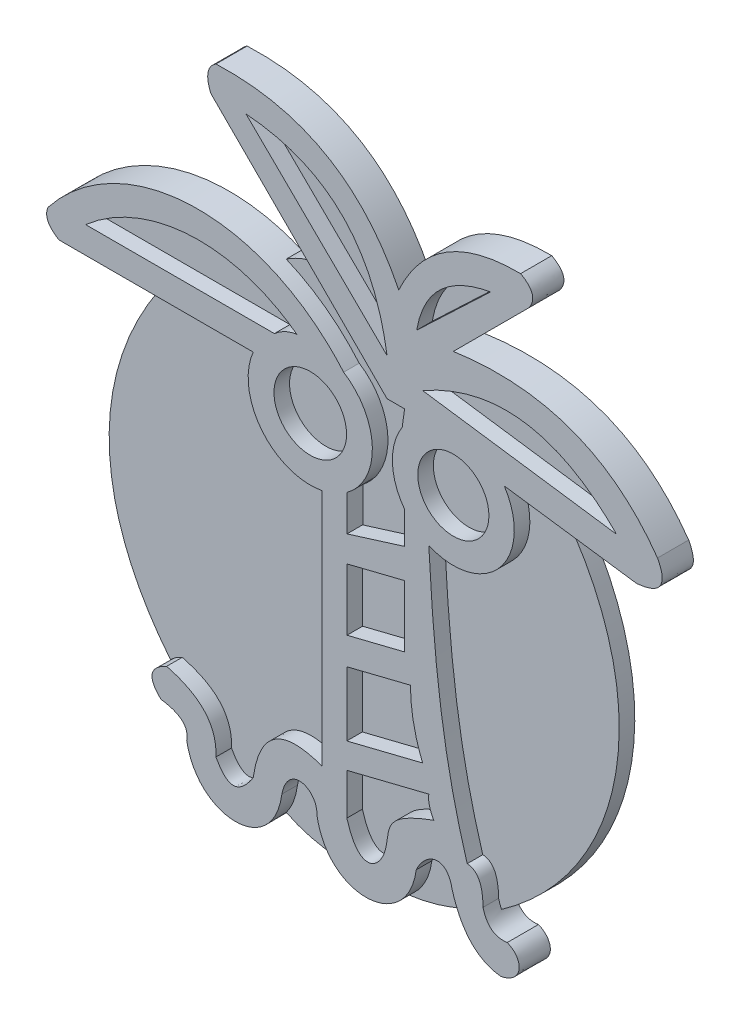
SolidWorks part; units mm, degrees
ref_plane "Plano frontal" through (0, 0, 0) normal (0, 0, 1) x (1, 0, 0)
ref_plane "Plano superior" through (0, 0, 0) normal (0, 1, 0) x (1, 0, 0)
ref_plane "Plano direito" through (0, 0, 0) normal (1, 0, 0) x (0, 0, -1)
sketch "Esboço1" plane through (0, 0, 0) normal (0, 0, 1) x (1, 0, 0)
  line L0 (-60.8884, 28.3736) -> (-123.2049, 28.3736)
  line L1 (-114.6677, 36.9122) -> (-54.103, 36.9122)
  line L2 (-38.7824, 0.9277) -> (-38.7824, -75.6639)
  line L3 (-30.8012, 4.4193) -> (-30.8012, -7.0977)
  line L4 (-30.8012, -7.0977) -> (-12.3205, -1.3392)
  line L5 (-12.3205, -1.3392) -> (-12.3205, 8.9725)
  line L6 (-30.8012, -15.4417) -> (-12.3205, -10.8474)
  line L7 (-12.3205, -10.8474) -> (-12.3205, -30.6673)
  line L8 (-12.3205, -30.6673) -> (-30.8012, -35.2616)
  line L9 (-30.8012, -35.2616) -> (-30.8012, -15.4417)
  line L10 (-30.8149, -44.0341) -> (-10.4456, -38.9702)
  line L11 (-6.5434, -58.6334) -> (-30.8763, -64.6826)
  line L12 (-30.8763, -64.6826) -> (-30.8149, -44.0341)
  line L13 (-30.8481, -72.8265) -> (-4.5532, -66.2896)
  line L14 (-30.8481, -72.8265) -> (-30.8481, -86.1095)
  line L15 (19.6685, 31.4554) -> (62.1381, 25.5784)
  line L16 (3.3205, 60.665) -> (27.6404, 84.9849)
  line L17 (-74.4586, 93.402) -> (-17.9451, 36.8885)
  line L18 (-17.9451, 36.8885) -> (-12.3205, 36.8885)
  line L19 (-12.3205, 36.8885) -> (-13.0844, 31.3682)
  line L20 (-63.2095, 93.402) -> (-17.9451, 48.8802)
  line L21 (-6.5434, 44.8627) -> (55.71, 36.024)
  line L22 (-8.4456, 60.665) -> (15.2667, 83.1633)
  arc A0 (-60.8884, 28.3736) -> (-38.7824, 0.9277) centre (-42.586, 20.4895) ccw
  circle A1 centre (-106.0634, -77.5387) radius 4.9451
  arc A3 (-4.5532, 2.8123) -> (19.6685, 31.4554) centre (3.3205, 20.7169) ccw
  arc A4 (-13.0844, 31.3682) -> (-12.3205, 8.9725) centre (3.3205, 20.7169) ccw
  circle A5 centre (-42.586, 20.4895) radius 11.6455
  circle A6 centre (3.3205, 20.7169) radius 11.4162
  arc A7 (-30.8012, 4.4193) -> (-31.8683, 37.2902) centre (-42.586, 20.4895) ccw
  spline S0 degree 3 poles (-126.6868, 35.7562) (-102.8055, 65.8868) (-57.2496, 68.1638) (-30.8012, 36.024) knots 0 0 0 0 1 1 1 1
  spline S1 degree 2 poles (-123.2049, 28.3736) (-128.5563, 31.5723) (-126.6868, 35.7562) knots 0 0 0 1 1 1
  spline S2 degree 3 poles (-114.6677, 36.9122) (-95.4732, 53.7124) (-67.6287, 55.71) (-46.8714, 40.3094) knots 0 0 0 0 1 1 1 1
  spline S3 degree 2 poles (-54.103, 36.9122) (-50.7611, 39.8144) (-46.8714, 40.3094) knots 0 0 0 1 1 1
  spline S4 degree 2 poles (-10.4456, -38.9702) (-10.4151, -49.1245) (-6.5434, -58.6334) knots 0 0 0 1 1 1
  spline S5 degree 2 poles (-4.5532, -66.2896) (-4.9343, -69.3953) (-2.9462, -72.7552) knots 0 0 0 1 1 1
  spline S6 degree 3 poles (-30.8481, -86.1095) (-27.1078, -99.4978) (-18.8735, -94.8712) (-17.4742, -81.1051) (-15.668, -77.3953) (-2.9462, -72.7552) knots 0 0 0 0 0.568309 0.668309 1 1 1 1
  spline S7 degree 3 poles (-4.5532, 2.8123) (-2.8793, -27.9871) (-0.2678, -53.0855) (7.7673, -79.468) knots 0 0 0 0 1 1 1 1
  spline S8 degree 2 poles (7.7673, -79.468) (12.7783, -79.7342) (12.8562, -89.0557) knots 0 0 0 1 1 1
  spline S9 degree 2 poles (12.8562, -89.0557) (14.5282, -95.7441) (20.6234, -94.9481) knots 0 0 0 1 1 1
  spline S10 degree 3 poles (20.6234, -94.9481) (26.2001, -97.1788) (25.846, -104.0546) (18.4807, -105.3938) knots 0 0 0 0 1 1 1 1
  spline S11 degree 2 poles (18.4807, -105.3938) (7.2976, -104.1184) (2.9462, -89.0557) knots 0 0 0 1 1 1
  spline S12 degree 3 poles (2.9462, -89.0557) (1.2727, -80.3537) (-5.6695, -82.8514) (-8.5708, -89.3236) knots 0 0 0 0 1 1 1 1
  spline S13 degree 3 poles (-8.5708, -89.3236) (-11.2487, -109.408) (-36.7608, -110.8833) (-40.4434, -90.1271) knots 0 0 0 0 1 1 1 1
  spline S14 degree 3 poles (-40.4434, -90.1271) (-40.1086, -83.0964) (-49.6838, -79.4808) (-51.6925, -89.8592) knots 0 0 0 0 1 1 1 1
  spline S15 degree 3 poles (-51.6925, -89.8592) (-54.3704, -110.2785) (-78.8779, -109.5451) (-82.2259, -90.1271) knots 0 0 0 0 1 1 1 1
  spline S16 degree 2 poles (-82.2259, -90.1271) (-81.1547, -84.2346) (-90.5288, -82.8955) knots 0 0 0 1 1 1
  spline S17 degree 2 poles (-90.5288, -82.8955) (-97.023, -76.7076) (-88.654, -72.8265) knots 0 0 0 1 1 1
  spline S18 degree 2 poles (-88.654, -72.8265) (-72.2554, -77.0412) (-72.8516, -90.1271) knots 0 0 0 1 1 1
  spline S19 degree 3 poles (-72.8516, -90.1271) (-69.5068, -96.3708) (-65.7853, -97.5389) (-60.8884, -89.8592) knots 0 0 0 0 1 1 1 1
  spline S20 degree 2 poles (-60.8884, -89.8592) (-57.9268, -68.6355) (-38.7824, -75.6639) knots 0 0 0 1 1 1
  spline S21 degree 2 poles (62.1381, 25.5784) (73.854, 26.6535) (68.834, 36.024) knots 0 0 0 1 1 1
  spline S22 degree 2 poles (68.834, 36.024) (47.0455, 67.0261) (3.3205, 60.665) knots 0 0 0 1 1 1
  spline S23 degree 2 poles (27.6404, 84.9849) (30.9295, 89.7285) (24.9088, 93.0733) knots 0 0 0 1 1 1
  spline S24 degree 2 poles (24.9088, 93.0733) (-2.8772, 93.408) (-14.1953, 68.968) knots 0 0 0 1 1 1
  spline S25 degree 2 poles (-14.1953, 68.968) (-31.6027, 104.1174) (-72.8516, 102.4476) knots 0 0 0 1 1 1
  spline S26 degree 2 poles (-72.8516, 102.4476) (-77.1364, 99.6857) (-74.4586, 93.402) knots 0 0 0 1 1 1
  spline S27 degree 2 poles (-63.2095, 93.402) (-24.306, 90.3936) (-17.9451, 48.8802) knots 0 0 0 1 1 1
  spline S28 degree 2 poles (-6.5434, 44.8627) (27.7496, 64.2807) (55.71, 36.024) knots 0 0 0 1 1 1
  spline S29 degree 2 poles (-8.4456, 60.665) (-5.1558, 79.4806) (15.2667, 83.1633) knots 0 0 0 1 1 1
sketch "Esboço2" plane through (0, 0, 0) normal (0, 0, 1) x (1, 0, 0)
  line L0 (-94.0107, 28.3736) -> (-60.8884, 28.3736)
  line L13 (-30.8481, -72.8265) -> (-30.8481, -86.1095)
  line L14 (-30.8481, -72.8265) -> (-4.5532, -66.2896)
  line L15 (-6.5434, -58.6334) -> (-30.8763, -64.6826)
  line L16 (-30.8763, -64.6826) -> (-30.8149, -44.0341)
  line L17 (-30.8149, -44.0341) -> (-10.4456, -38.9702)
  line L18 (-30.8012, -35.2616) -> (-30.8012, -15.4417)
  line L19 (-12.3205, -10.8474) -> (-12.3205, -30.6673)
  line L20 (-12.3205, -30.6673) -> (-30.8012, -35.2616)
  line L21 (-30.8012, -15.4417) -> (-12.3205, -10.8474)
  line L22 (-114.6677, 36.9122) -> (-54.103, 36.9122)
  line L23 (-6.5434, 44.8627) -> (55.71, 36.024)
  line L24 (-8.4456, 60.665) -> (15.2667, 83.1633)
  line L25 (-63.2095, 93.402) -> (-17.9451, 48.8802)
  line L26 (19.6685, 31.4554) -> (62.1381, 25.5784) construction
  line L27 (-74.4586, 93.402) -> (-17.9451, 36.8885) construction
  line L28 (-60.8884, 28.3736) -> (-123.2049, 28.3736) construction
  line L35 (-30.6705, 4.2481) -> (-30.6705, -7.2689)
  line L36 (-30.6705, -7.2689) -> (-12.1897, -1.5104)
  line L37 (-12.1897, -1.5104) -> (-12.1897, 8.8013)
  line L38 (-12.3205, 36.8885) -> (-13.0844, 31.3682)
  line L39 (-17.9451, 36.8885) -> (-12.3205, 36.8885)
  line L40 (-39.6094, 58.5528) -> (-17.9451, 36.8885)
  line L41 (19.6685, 31.4554) -> (33.2461, 29.5765)
  line L42 (-38.7824, 0.9277) -> (-38.7824, -75.6639)
  arc A0 (-30.6705, 4.2481) -> (-30.8012, 36.024) centre (-42.7649, 20.0866) ccw
  circle A2 centre (-42.586, 20.4895) radius 11.6455
  circle A3 centre (3.3205, 20.7169) radius 11.4162
  arc A7 (-13.0844, 31.3682) -> (-12.1897, 8.8013) centre (3.3208, 20.7174) ccw
  arc A8 (-4.5532, 2.8123) -> (19.6685, 31.4554) centre (3.3205, 20.7169) ccw
  arc A9 (-60.8884, 28.3736) -> (-38.7824, 0.5604) centre (-42.7649, 20.0866) ccw
  parabola Q1 (-92.3862, -75.4203) -> (-88.654, -72.8265) focus (-91.6035, -77.6549) apex (-93.3248, -77.3878)
  parabola Q2 (12.8562, -89.0557) -> (13.8144, -91.6525) focus (17.5255, -91.8997) apex (16.1532, -94.2218)
  parabola Q3 (7.7673, -79.468) -> (12.8562, -89.0557) focus (8.7018, -81.7241) apex (9.6529, -79.9783)
  parabola Q6 (-4.5532, -66.2896) -> (-2.9462, -72.7552) focus (-0.483, -66.852) apex (-4.5675, -66.4138)
  parabola Q7 (-10.4456, -38.9702) -> (-6.5434, -58.6334) focus (15.6869, -43.1994) apex (-9.7284, -47.4697)
  parabola Q8 (-54.103, 36.9122) -> (-46.8714, 40.3094) focus (-46.6878, 34.0843) apex (-48.0565, 40.0998)
  parabola Q9 (-6.5434, 44.8627) -> (55.71, 36.024) focus (23.095, 32.0411) apex (25.8009, 52.4122)
  parabola Q10 (-8.4456, 60.665) -> (15.2667, 83.1633) focus (6.3926, 66.5452) apex (-2.2975, 74.221)
  parabola Q11 (-63.2095, 93.402) -> (-17.9451, 48.8802) focus (-47.4933, 67.6135) apex (-34.6635, 82.794)
  parabola Q12 (12.8562, -89.0557) -> (20.6234, -94.9481) focus (17.5255, -91.8997) apex (16.1532, -94.2218) construction
  parabola Q14 (18.4807, -105.3938) -> (2.9462, -89.0557) focus (16.5802, -97.3827) apex (13.3462, -103.9093) construction
  parabola Q21 (5.4072, -95.45) -> (2.9462, -89.0557) focus (16.5802, -97.3827) apex (13.3462, -103.9093)
  parabola Q23 (-88.654, -72.8265) -> (-72.8516, -90.1271) focus (-80.377, -85.2807) apex (-74.4466, -82.185)
  parabola Q24 (-60.8884, -89.8592) -> (-38.7824, -75.6639) focus (-50.7954, -80.0071) apex (-53.4228, -75.4203)
  spline S0 degree 3 poles (-92.3862, -75.4203) (-118.7369, -43.0379) (-118.1056, -4.9029) (-94.0107, 28.3736) knots 0 0 0 0 1 1 1 1
  spline S2 degree 3 poles (-30.8481, -86.1095) (-27.1078, -99.4978) (-18.8735, -94.8712) (-17.4742, -81.1051) (-15.668, -77.3953) (-2.9462, -72.7552) knots 0 0 0 0 0.568309 0.668309 1 1 1 1
  spline S3 degree 3 poles (-114.6677, 36.9122) (-95.4732, 53.7124) (-67.6287, 55.71) (-46.8714, 40.3094) knots 0 0 0 0 1 1 1 1
  spline S4 degree 3 poles (33.2461, 29.5765) (63.6692, -9.9045) (55.4699, -62.2929) (13.8144, -91.6525) knots 0 0 0 0 1 1 1 1
  spline S5 degree 2 poles (-39.6094, 58.5528) (-47.6778, 59.5185) (-55.2829, 54.5266) knots 0 0 0 1 1 1
  spline S6 degree 3 poles (-126.6868, 35.7562) (-102.8055, 65.8868) (-57.2496, 68.1638) (-30.8012, 36.024) knots 0 0 0 0 1 1 1 1 construction
  spline S8 degree 2 poles (-55.2829, -99.2173) (-45.4416, -104.2577) (-30.8481, -103.7418) knots 0 0 0 1 1 1
  spline S9 degree 3 poles (-51.6925, -89.8592) (-54.3704, -110.2785) (-78.8779, -109.5451) (-82.2259, -90.1271) knots 0 0 0 0 1 1 1 1 construction
  spline S10 degree 3 poles (-8.5708, -89.3236) (-11.2487, -109.408) (-36.7608, -110.8833) (-40.4434, -90.1271) knots 0 0 0 0 1 1 1 1 construction
  spline S11 degree 2 poles (-16.4154, -102.595) (-4.6055, -101.0721) (5.4072, -95.45) knots 0 0 0 1 1 1
  spline S16 degree 3 poles (-55.2829, 54.5266) (-46.2783, 50.727) (-37.8594, 44.601) (-30.8012, 36.024) knots 0.733135 0.733135 0.733135 0.733135 1 1 1 1
  spline S17 degree 3 poles (-4.5532, 2.8123) (-2.8793, -27.9871) (-0.2678, -53.0855) (7.7673, -79.468) knots 0 0 0 0 1 1 1 1
  spline S18 degree 3 poles (2.9462, -89.0557) (1.2727, -80.3537) (-5.6695, -82.8514) (-8.5708, -89.3236) knots 0 0 0 0 1 1 1 1
  spline S19 degree 3 poles (-8.5708, -89.3236) (-9.4082, -95.6039) (-12.4782, -100.0646) (-16.4154, -102.595) knots 0 0 0 0 0.312696 0.312696 0.312696 0.312696
  spline S20 degree 3 poles (-40.4434, -90.1271) (-40.1086, -83.0964) (-49.6838, -79.4808) (-51.6925, -89.8592) knots 0 0 0 0 1 1 1 1
  spline S21 degree 3 poles (-51.6925, -89.8592) (-52.2008, -93.7351) (-53.4956, -96.8488) (-55.2829, -99.2173) knots 0 0 0 0 0.189813 0.189813 0.189813 0.189813
  spline S22 degree 3 poles (-72.8516, -90.1271) (-69.5068, -96.3708) (-65.7853, -97.5389) (-60.8884, -89.8592) knots 0 0 0 0 1 1 1 1
  spline S23 degree 3 poles (-30.8481, -103.7418) (-35.4024, -101.6871) (-39.1891, -97.1966) (-40.4434, -90.1271) knots 0.6594 0.6594 0.6594 0.6594 1 1 1 1
  point P48 (12.8562, -89.0557)
  point P51 (0, 0)
extrude "Ressalto-extrusão1" add sketch "Esboço1" along normal blind 10
extrude "Ressalto-extrusão2" add sketch "Esboço2" along normal blind 5 contours Q23 S22 Q24 L42 A9 L0 S0 Q1 | A8 S17 Q3 Q2 S4 L41 | S8 S23 S20 S21 | S18 S19 S11 Q21 | L13 S2 Q6 L14 | Q7 L17 L16 L15 | L21 L18 L20 L19 | S5 S16 A0 L35 L36 L37 A7 L38 L39 L40 | A2 | S3 L22 Q8 | Q11 L25 | Q10 L24 | Q9 L23 | A3
